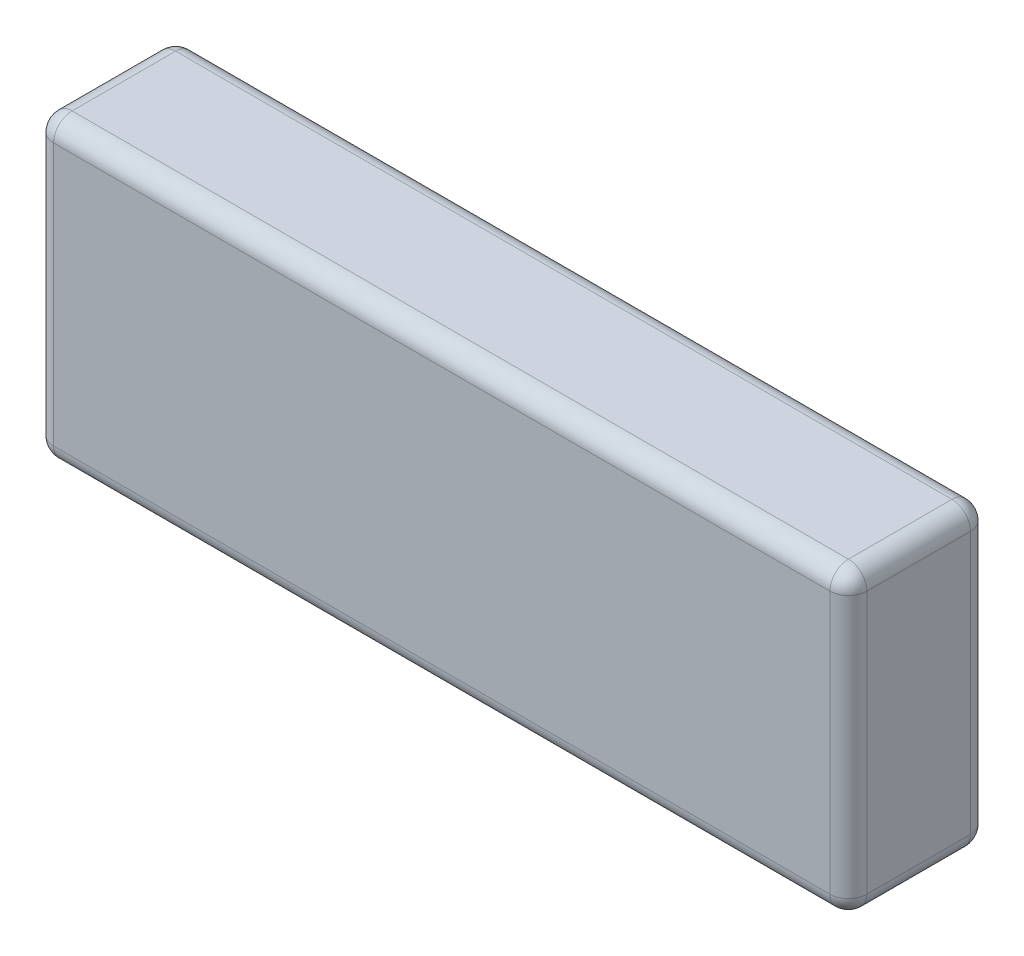
SolidWorks part; units mm, degrees
ref_plane "Front Plane" through (0, 0, 0) normal (0, 0, 1) x (1, 0, 0)
ref_plane "Top Plane" through (0, 0, 0) normal (0, 1, 0) x (1, 0, 0)
ref_plane "Right Plane" through (0, 0, 0) normal (1, 0, 0) x (0, 0, -1)
sketch "Sketch1" plane through (0, 0, 0) normal (0, 0, 1) x (1, 0, 0)
  line L1 (0, 0) -> (22, 0)
  line L2 (0, 0) -> (0, 8.1)
  line L3 (0, 8.1) -> (22, 8.1)
  line L4 (22, 0) -> (22, 8.1)
  dimension "D1" = 8.1
  dimension "D2" = 22
extrude "Boss-Extrude1" add sketch "Sketch1" along normal blind 3.8
fillet "Fillet1" radius 0.5 12 edges at (0, 0, 1.9) (11, 0, 0) (0, 4.05, 0) (22, 0, 1.9) (22, 4.05, 0) (22, 8.1, 1.9) (0, 8.1, 1.9) (11, 8.1, 0) (11, 8.1, 3.8) (22, 4.05, 3.8) (11, 0, 3.8) (0, 4.05, 3.8)
